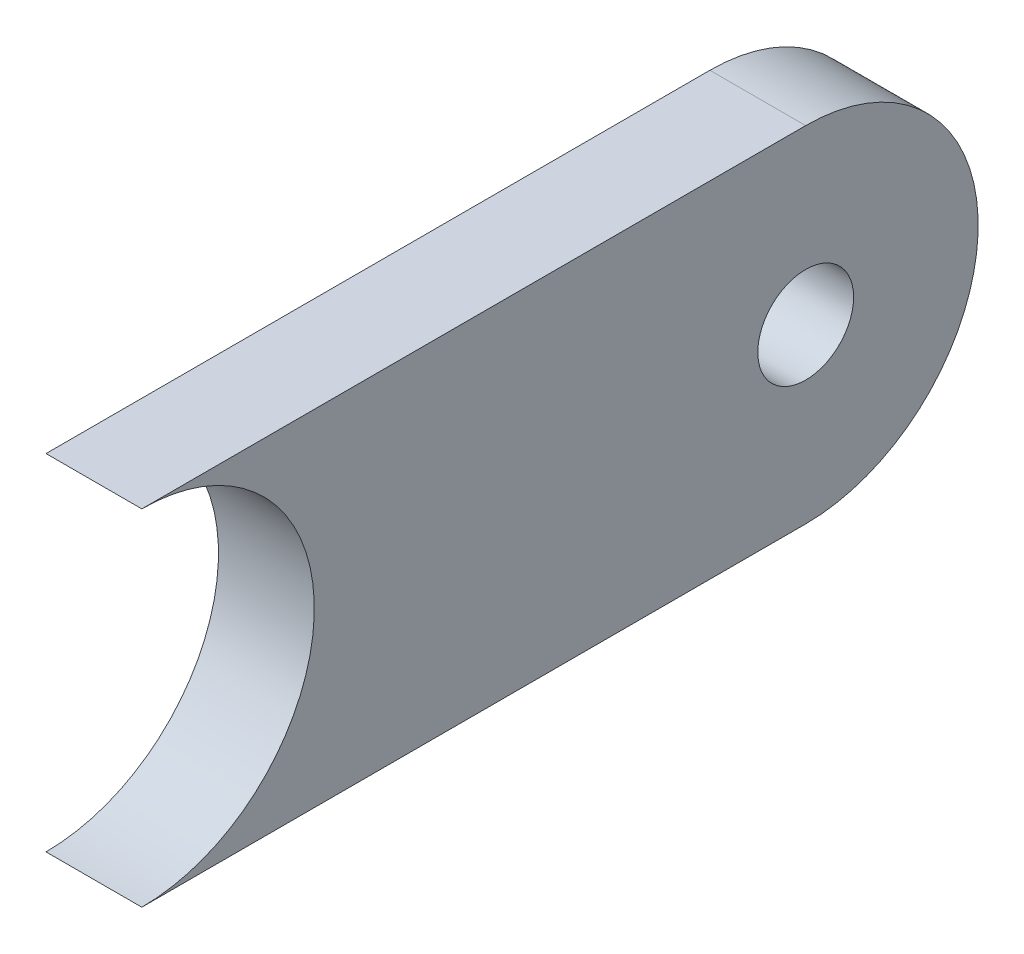
SolidWorks part; units mm, degrees
ref_plane "前基準面" through (0, 0, 0) normal (0, 0, 1) x (1, 0, 0)
ref_plane "上基準面" through (0, 0, 0) normal (0, 1, 0) x (1, 0, 0)
ref_plane "右基準面" through (0, 0, 0) normal (1, 0, 0) x (0, 0, -1)
sketch "草圖3" plane through (0, 0, 0) normal (1, 0, 0) x (0, 0, -1)
  line L0 (0, -9) -> (-34.64, -9)
  line L1 (-34.64, 9) -> (0, 9)
  arc A0 (0, -9) -> (0, 9) centre (0, 0) ccw
  arc A1 (-34.64, -9) -> (-34.64, 9) centre (-34.64, 0) ccw
  circle A2 centre (0, 0) radius 2.5
  dimension "D2" = 18
  dimension "D3" = 18
  dimension "D4" = 5
  dimension "D1" = 34.64
extrude "填料-伸長3" add sketch "草圖3" along normal blind 5
